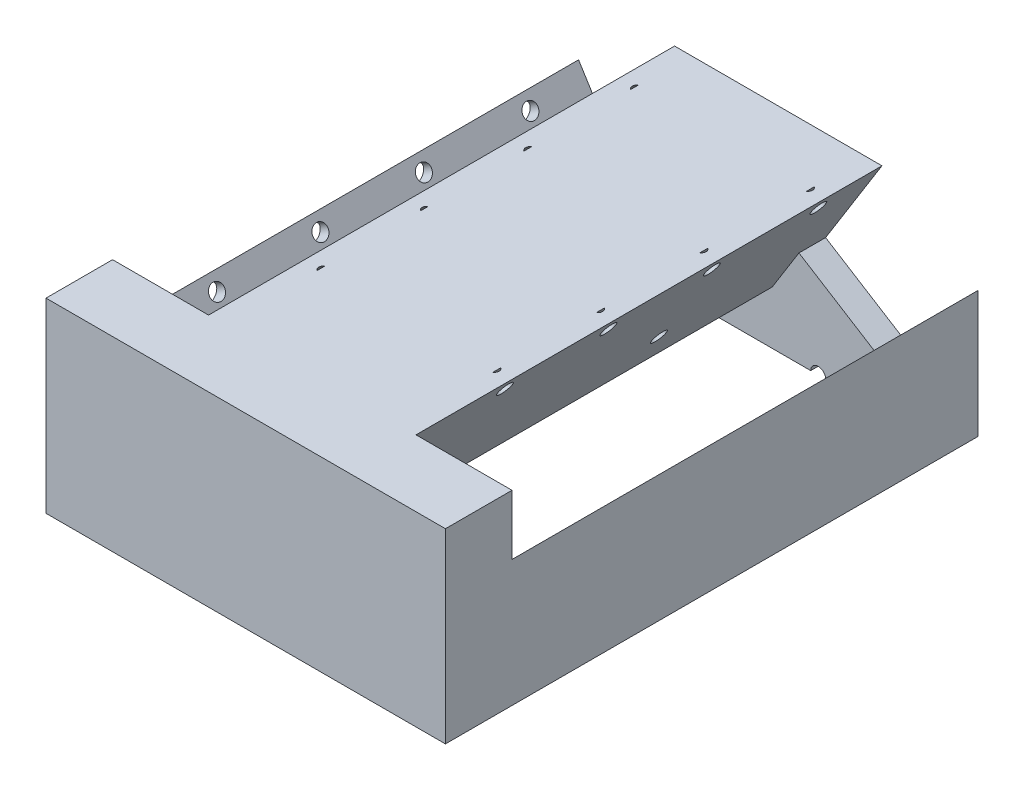
SolidWorks part; units mm, degrees
ref_plane "前视基准面" through (0, 0, 0) normal (0, 0, 1) x (1, 0, 0)
ref_plane "上视基准面" through (0, 0, 0) normal (0, 1, 0) x (1, 0, 0)
ref_plane "右视基准面" through (0, 0, 0) normal (1, 0, 0) x (0, 0, -1)
sketch "草图1" plane through (0, 0, 0) normal (0, 0, 1) x (1, 0, 0)
  line L1 (0, 0) -> (30, 0)
  line L2 (0, 0) -> (0, -14)
  line L3 (0, -14) -> (30, -14)
  line L4 (30, 0) -> (30, -14)
  dimension "D1" = 30
  dimension "D2" = 14
extrude "凸台-拉伸1" add sketch "草图1" along normal blind 40
sketch "草图3" plane through (0, 0, 0) normal (0, 0, -1) x (-1, 0, 0)
  line L0 (-30, -4.5) -> (-25.7647, -11.2869)
  line L1 (-30, -14) -> (-30, 0) construction
  line L2 (-25.7647, -11.2869) -> (-18.5536, -6.7869)
  line L3 (-18.5536, -6.7869) -> (-22.7889, 0)
  line L4 (-30, 0) -> (0, 0) construction
  line L5 (-7.2111, 0) -> (-11.4464, -6.7869)
  line L6 (-11.4464, -6.7869) -> (-4.2353, -11.2869)
  line L7 (-4.2353, -11.2869) -> (0, -4.5)
  line L8 (0, 0) -> (0, -14) construction
  line L9 (0, 0) -> (0, -4.5)
  line L10 (-30, 0) -> (-22.7889, 0)
  line L11 (-30, -4.5) -> (-30, 0)
  line L12 (-7.2111, 0) -> (0, 0)
  dimension "D1" = 8.5
  dimension "D2" = 8.5
  dimension "D3" = 8
  dimension "D4" = 4.5
extrude "切除-拉伸1" cut sketch "草图3" against normal blind 35
sketch "草图4" plane through (0, -14, 0) normal (0, -1, 0) x (1, 0, 0)
  line L1 (1.5, 38) -> (28.5, 38)
  line L2 (1.5, 38) -> (1.5, 2)
  line L3 (1.5, 2) -> (28.5, 2)
  line L4 (28.5, 38) -> (28.5, 2)
  line L5 (0, 40) -> (30, 40) construction
  line L6 (30, 40) -> (30, 0) construction
  point P9 (15, 40)
  point P10 (15, 38)
  point P11 (30, 20)
  point P14 (28.5, 20)
  dimension "D1" = 1.5
  dimension "D2" = 2
extrude "切除-拉伸2" cut sketch "草图4" against normal up to vertex (7.2131 mm away) up to point (11.4464, -6.7869, 0)
sketch "草图5" plane through (0, 0, 0) normal (0, 0, -1) x (-1, 0, 0)
  line L0 (0, -14) -> (-30, -14) construction
  circle A0 centre (-10, -14) radius 0.565
  circle A1 centre (-20, -14) radius 0.565
  dimension "D2" = 1.13
  dimension "D4" = 1.13
  dimension "D1" = 10
  dimension "D3" = 10
extrude "切除-拉伸3" cut sketch "草图5" against normal blind 10
sketch "草图7" plane through (0, 0, 0) normal (0, 0, -1) x (-1, 0, 0)
  line L0 (-22.7889, 0) -> (-18.5536, -6.7869)
  line L1 (-18.5536, -6.7869) -> (-16.5485, -10)
  line L2 (-16.5485, -10) -> (-13.4515, -10)
  line L3 (-7.2111, 0) -> (-11.4464, -6.7869)
  line L4 (-11.4464, -6.7869) -> (-13.4515, -10)
  line L5 (-22.7889, 0) -> (-7.2111, 0)
  dimension "D1" = 4
extrude "凸台-拉伸2" add sketch "草图7" against normal up to next
sketch "草图6" plane through (5.19, 3.2388, 0) normal (-0.8484, -0.5294, 0) x (0, 0, 1)
  circle A0 centre (12.2, -12.4176) radius 0.565
  circle A1 centre (12.2, -4.9176) radius 0.565
  circle A2 centre (4.2, -4.9176) radius 0.565
  circle A3 centre (19.97, -4.9176) radius 0.565
  circle A4 centre (27.74, -4.9176) radius 0.565
  point P11 (0, 0)
  point P12 (0, 0)
  dimension "D1" = 1.13
  dimension "D4" = 1.13
  dimension "D6" = 1.13
  dimension "D8" = 1.13
  dimension "D9" = 1.13
  dimension "D2" = 12.2
  dimension "D3" = 8.6
  dimension "D5" = 7.5
  dimension "D7" = 8
  dimension "D10" = 7.77
  dimension "D11" = 7.77
extrude "切除-拉伸4" cut sketch "草图6" against normal blind 1
ref_plane "基准面1" through (15, 0, 0) normal (1, 0, 0) x (0, 0, -1)
mirror "镜向1" about plane through (15, 0, 0) normal (1, 0, 0) of "切除-拉伸4"
sketch "草图8" plane through (5.19, 3.2388, 0) normal (-0.8484, -0.5294, 0) x (0, 0, 1)
  circle A0 centre (12.2, -12.4176) radius 0.565 construction
  circle A1 centre (12.2, -12.4176) radius 0.565
  circle A2 centre (4.2, -4.9176) radius 0.565 construction
  circle A3 centre (4.2, -4.9176) radius 0.565
  circle A4 centre (27.74, -4.9176) radius 0.565 construction
  circle A5 centre (19.97, -4.9176) radius 0.565 construction
  circle A6 centre (12.2, -4.9176) radius 0.565 construction
  circle A7 centre (27.74, -4.9176) radius 0.565
  circle A8 centre (19.97, -4.9176) radius 0.565
  circle A9 centre (12.2, -4.9176) radius 0.565
extrude "切除-拉伸5" cut sketch "草图8" along normal through all
